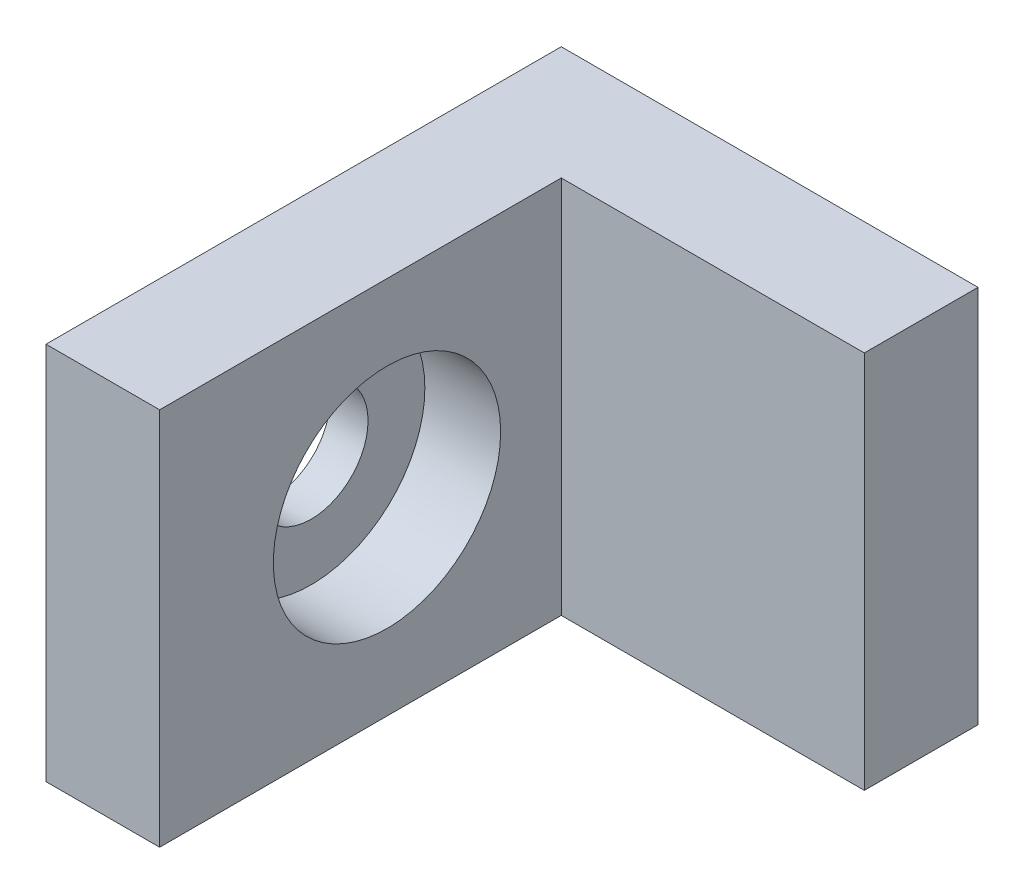
SolidWorks part; units mm, degrees
ref_plane "前视基准面" through (0, 0, 0) normal (0, 0, 1) x (1, 0, 0)
ref_plane "上视基准面" through (0, 0, 0) normal (0, 1, 0) x (1, 0, 0)
ref_plane "右视基准面" through (0, 0, 0) normal (1, 0, 0) x (0, 0, -1)
other "Configuration Table"
sketch "草图1" plane through (0, 0, 0) normal (1, 0, 0) x (0, 0, -1)
  line L1 (0, 0) -> (-16, 0)
  line L2 (0, 0) -> (0, 10)
  line L3 (0, 10) -> (-16, 10)
  line L4 (-16, 0) -> (-16, 10)
  dimension "D1" = 16
  dimension "D2" = 10
extrude "凸台-拉伸1" add sketch "草图1" along normal blind 3
sketch "草图2" plane through (3, 0, 0) normal (1, 0, 0) x (0, 0, -1)
  line L0 (0, 10) -> (-16, 10) construction
  line L1 (-0.4, 10) -> (-3.4, 10)
  line L2 (-0.4, 10) -> (-0.4, 0)
  line L3 (-0.4, 0) -> (-3.4, 0)
  line L4 (-3.4, 10) -> (-3.4, 0)
  line L5 (-16, 0) -> (0, 0) construction
  line L6 (0, 0) -> (0, 10) construction
  dimension "D1" = 0.4
  dimension "D2" = 3
extrude "凸台-拉伸2" add sketch "草图2" along normal blind 8
sketch "草图3" plane through (3, 0, 0) normal (1, 0, 0) x (0, 0, -1)
  line L0 (0, 10) -> (-10, 10) construction
  line L1 (-3.4, 10) -> (-16, 10) construction
  line L2 (-10, 10) -> (-10, 5) construction
  circle A1 centre (-10, 5) radius 1.5
  dimension "D2" = 5
  dimension "D3" = 3
  dimension "D1" = 10
extrude "切除-拉伸1" cut sketch "草图3" against normal blind 3
sketch "草图5" plane through (3, 0, 0) normal (1, 0, 0) x (0, 0, -1)
  circle A0 centre (-10, 5) radius 3
  dimension "D1" = 6
extrude "切除-拉伸3" cut sketch "草图5" against normal blind 2
sketch "草图7" plane through (3, 0, 0) normal (1, 0, 0) x (0, 0, -1)
  line L4 (-0.4, 10) -> (-0.4, 0)
  line L5 (-0.4, 0) -> (0, 0)
  line L6 (0, 0) -> (0, 10)
  line L7 (0, 10) -> (-0.4, 10)
  line L8 (-0.4, 10) -> (-0.4, 0)
  line L9 (-0.4, 0) -> (0, 0)
  line L10 (0, 0) -> (0, 10)
  line L11 (0, 10) -> (-0.4, 10)
  dimension "D1" = 0
extrude "切除-拉伸4" cut sketch "草图7" against normal blind 22
sketch "草图8" plane through (0, 0, 0.4) normal (0, 0, -1) x (-1, 0, 0)
  line L0 (0, 5) -> (-7.8, 5) construction
  line L1 (0, 10) -> (0, 0) construction
  circle A0 centre (-7.8, 5) radius 2.1
  dimension "D2" = 4.2
  dimension "D1" = 7.8
extrude "切除-拉伸5" cut sketch "草图8" against normal blind 4.2
sketch "草图9" plane through (0, 0, 3.4) normal (0, 0, 1) x (1, 0, 0)
  line L4 (3, 10) -> (3, 0)
  line L5 (3, 0) -> (11, 0)
  line L6 (11, 0) -> (11, 10)
  line L7 (11, 10) -> (3, 10)
  line L8 (3, 10) -> (3, 0)
  line L9 (3, 0) -> (11, 0)
  line L10 (11, 0) -> (11, 10)
  line L11 (11, 10) -> (3, 10)
  dimension "D1" = 0
extrude "凸台-拉伸3" add sketch "草图9" along normal blind 2
sketch "草图10" plane through (0, 0, 0.4) normal (0, 0, -1) x (-1, 0, 0)
  line L4 (-11, 0) -> (0, 0)
  line L5 (0, 0) -> (0, 10)
  line L6 (0, 10) -> (-11, 10)
  line L7 (-11, 10) -> (-11, 0)
  line L8 (-11, 0) -> (0, 0)
  line L9 (0, 0) -> (0, 10)
  line L10 (0, 10) -> (-11, 10)
  line L11 (-11, 10) -> (-11, 0)
  dimension "D1" = 0
extrude "切除-拉伸6" cut sketch "草图10" against normal blind 2
fillet "圆角1" radius 0.4 1 edges at (7.8, 7.1, 2.4)
